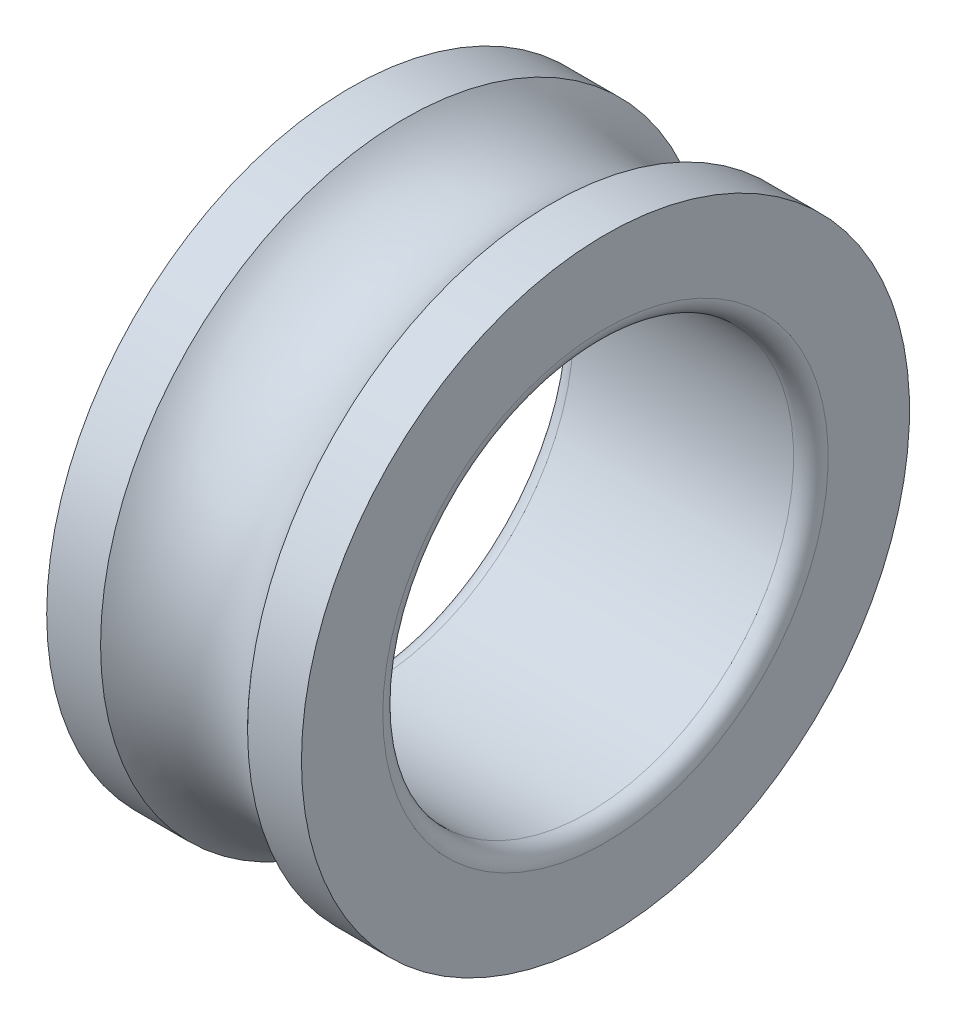
SolidWorks part; units mm, degrees
ref_plane "Front Plane" through (0, 0, 0) normal (0, 0, 1) x (1, 0, 0)
ref_plane "Top Plane" through (0, 0, 0) normal (0, 1, 0) x (1, 0, 0)
ref_plane "Right Plane" through (0, 0, 0) normal (1, 0, 0) x (0, 0, -1)
sketch "Sketch1" plane through (0, 0, 0) normal (0, 0, 1) x (1, 0, 0)
  line L0 (-135.1282, 0) -> (313.9744, 0) construction
  line L1 (0, 250) -> (0, 0) construction
  line L2 (134, 250) -> (-134, 250)
  line L3 (155, 271) -> (155, 370)
  line L4 (155, 370) -> (89.4427, 370)
  line L5 (-155, 271) -> (-155, 370)
  line L6 (155, 250) -> (-155, 370) construction
  line L7 (155, 370) -> (-155, 250) construction
  line L8 (-89.4427, 370) -> (-155, 370)
  arc A0 (-89.4427, 370) -> (89.4427, 370) centre (0, 450) ccw
  arc A1 (134, 250) -> (155, 271) centre (134, 271) ccw
  arc A2 (-134, 250) -> (-155, 271) centre (-134, 271) cw
  point P3 (0, 310)
  dimension "D5" = 120
  dimension "D6" = 21
  dimension "D1" = 310
  dimension "D2" = 250
  dimension "D3" = 370
  dimension "D4" = 80
revolve "Revolve1" add sketch "Sketch1" angle 360 about L0
